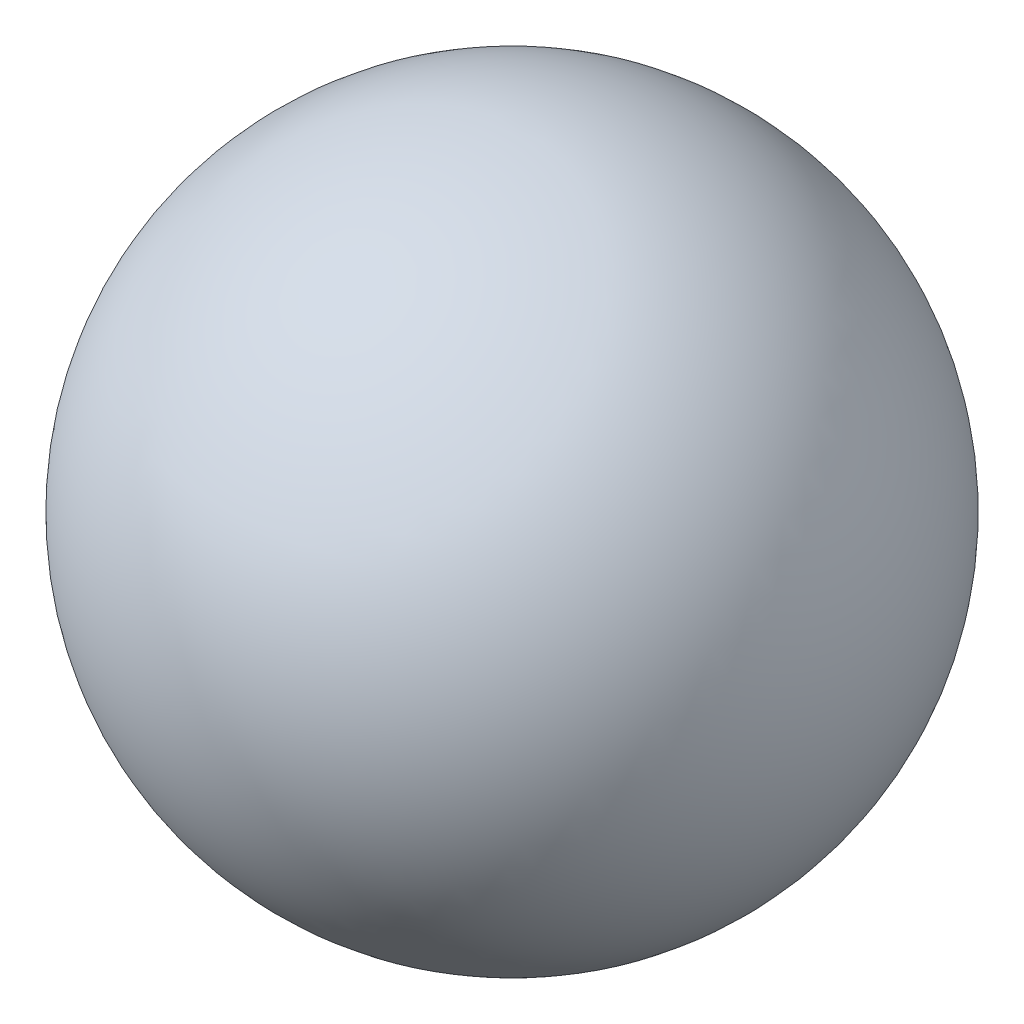
SolidWorks part; units mm, degrees
ref_plane "Front Plane" through (0, 0, 0) normal (0, 0, 1) x (1, 0, 0)
ref_plane "Top Plane" through (0, 0, 0) normal (0, 1, 0) x (1, 0, 0)
ref_plane "Right Plane" through (0, 0, 0) normal (1, 0, 0) x (0, 0, -1)
other "Configuration Table"
sketch "Sketch1" plane through (0, 0, 0) normal (0, 0, 1) x (1, 0, 0)
  line L0 (0, 37) -> (0, 36) construction
  line L1 (0, 37) -> (0, 36)
  line L3 (0, -36) -> (0, -37)
  arc A0 (0, 37) -> (0, -37) centre (0, 0) cw
  arc A1 (0, 36) -> (0, -36) centre (0, 0) cw
  dimension "D1" = 74
  dimension "D2" = 1
revolve "Revolve1" add sketch "Sketch1" angle 360 about L0
